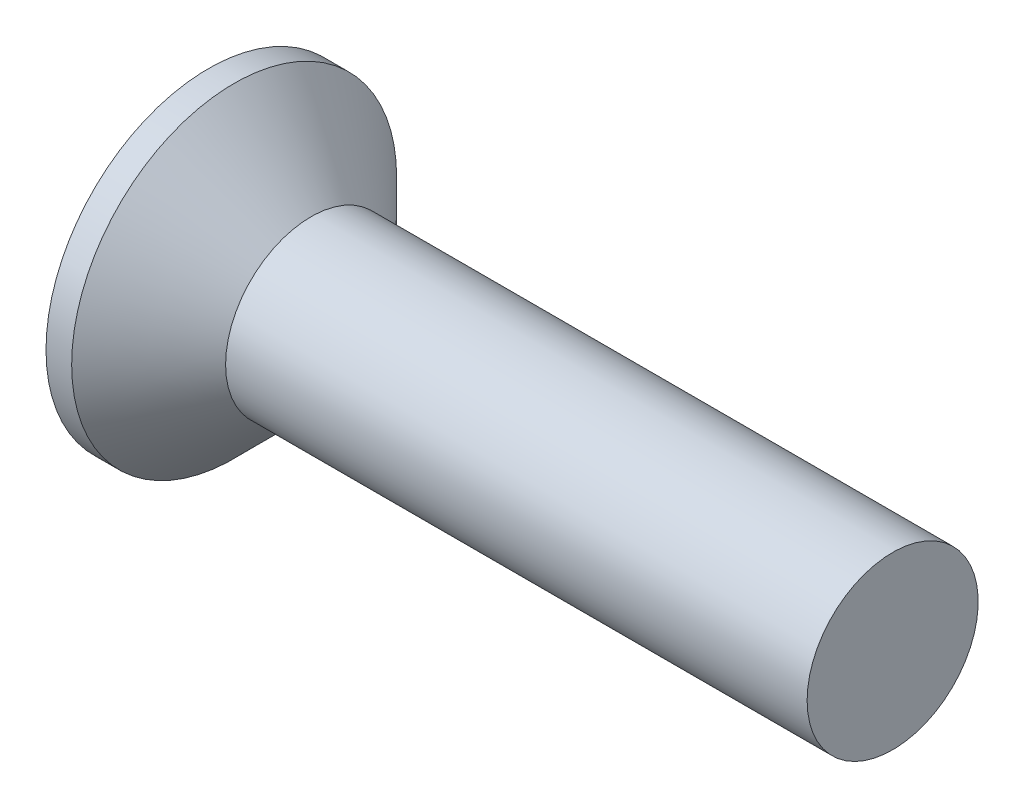
SolidWorks part; units mm, degrees
revolve "Base-Revolve" add sketch "BodySke" angle 360 about L5
sketch "BodySke" plane through (0, 0, 0) normal (0, 0, 1) x (1, 0, 0)
  line L0 (0, 0) -> (0, 1.9)
  line L1 (0, 1.9) -> (0.3, 1.9)
  line L2 (1.2, 1) -> (8, 1)
  line L3 (8, 1) -> (8, 0)
  line L4 (8, 0) -> (0, 0)
  line L5 (-6.35, 0) -> (82.55, 0) construction
  line L6 (1.2, -1) -> (8, -1) construction
  line L7 (0.3, -1.9) -> (1.2, -1) construction
  line L8 (0.3, 1.9) -> (1.2, 1)
  line L9 (0, -1.9) -> (0.3, -1.9) construction
  line L10 (1.6, 2.5875) -> (1.6, -6.9375) construction
  line L11 (5, 6.35) -> (5, -3.175) construction
  dimension "Diameter" = 2
  dimension "Length" = 8
  dimension "Head_ht" = 1.2
  dimension "Head_dia" = 3.8
  dimension "Head_ang" = 90
  dimension "D6" = 0.3
  dimension "Advance" = 0.4
cosmetic thread "ThreadCosmetic" [suppressed] parameters "Thread_length"=6.4, "Thread_minor"=1.548
extrude "Slot" [suppressed] cut sketch "Sketch2" against normal blind 0.6
sketch "Sketch2" plane through (0, 0, 0) normal (-1, 0, 0) x (0, 0, 1)
  line L0 (-1.9, -0.35) -> (1.9, -0.35)
  line L1 (-1.9, -0.35) -> (-1.9, 0.35)
  line L2 (1.9, 0.35) -> (-1.9, 0.35)
  line L3 (1.9, 0.35) -> (1.9, -0.35)
  dimension "Slot_width" = 0.7
  dimension "D1" = 0.35
  dimension "D2" = 3.8
  dimension "D3" = 1.9
ref_plane "Plane1" through (0, 0, 0) normal (0, 0, 1) x (1, 0, 0)
ref_plane "Plane2" through (0, 0, 0) normal (0, 1, 0) x (1, 0, 0)
ref_plane "Plane3" through (0, 0, 0) normal (1, 0, 0) x (0, 0, -1)
sketch "Sketch3" plane through (0, 0, 0) normal (-1, 0, 0) x (0, 0, 1)
  line L0 (-0.265, 1.07) -> (0.265, 1.07)
  line L1 (0.265, 1.07) -> (0.265, -1.07)
  line L2 (0.265, -1.07) -> (-0.265, -1.07)
  line L3 (-0.265, -1.07) -> (-0.265, 1.07)
  dimension "Cross_dia" = 2.14
  dimension "Cross_width" = 0.53
  dimension "D1" = 1.07
  dimension "D2" = 0.265
ref_plane "Plane4" through (1.54, 0, 0) normal (-1, 0, 0) x (0, 0, 1)
sketch "Sketch4" plane through (1.54, 0, 0) normal (-1, 0, 0) x (0, 0, 1)
  line L0 (-0.1325, 0.1325) -> (0.1325, 0.1325)
  line L3 (0.1325, 0.1325) -> (0.1325, -0.1325)
  line L4 (0.1325, -0.1325) -> (-0.1325, -0.1325)
  line L5 (-0.1325, -0.1325) -> (-0.1325, 0.1325)
  dimension "D2" = 0.265
  dimension "D1" = 0.265
  dimension "D3" = 0.1325
  dimension "D4" = 0.1325
loft "Cross" [suppressed] cut profiles "Sketch3", "Sketch4"
pattern_circular "CirPattern1" [suppressed] count 2 every 90 about axis through (-6.35, 0, 0) along (1, 0, 0)
sketch "ThdSchSke" plane through (0, 0, 0) normal (0, 0, 1) x (1, 0, 0)
  line L0 (5, -0.774) -> (4.8418, -1)
  line L1 (5, -0.774) -> (5.1582, -1)
  line L2 (5.1582, -1) -> (5.1582, -1.25)
  line L3 (-3.175, 0) -> (5.1513, 0) construction
  line L5 (5.1582, -1.25) -> (4.8418, -1.25)
  line L6 (4.8418, -1.25) -> (4.8418, -1)
  line L7 (0, 1.9) -> (0, -1.9) construction
  dimension "Diameter" = 2
  dimension "Thread_minor" = 1.548
  dimension "Start" = 1.6
revolve "ThreadSchematic" [suppressed] cut sketch "ThdSchSke" angle 360 about L3
pattern_linear "ThdSchPat" [suppressed]
equation "\"D1@Sketch3\" = \"Cross_dia@Sketch3\" / 2"
equation "\"D2@Sketch3\" = \"Cross_width@Sketch3\" / 2"
equation "\"D1@Sketch4\" = \"Cross_width@Sketch3\" *.5"
equation "\"D2@Sketch4\" = \"D1@Sketch4\""
equation "\"D4@Sketch4\" = \"D2@Sketch4\" / 2"
equation "\"D3@Sketch4\" = \"D1@Sketch4\" / 2"
equation "\"D1@Sketch2\" = \"Slot_width@Sketch2\" / 2"
equation "\"D2@Sketch2\" = \"Head_dia@BodySke\""
equation "\"D3@Sketch2\" = \"D2@Sketch2\" / 2"
equation "\"Thread_length@ThreadCosmetic\" = ((sgn( (\"Length@BodySke\" - \"Advance@BodySke\" - \"Head_ht@BodySke\" ) - \"Thread_nom@BodySke\" )-1)*( (\"Length@BodySke\" - \"Advance@BodySke\" - \"Head_ht@BodySke\" ) - \"Thread_nom@BodySke\" ))/-2+ \"Thread_nom@BodySke\""
equation "\"Thread_minor@ThdSchSke\" = \"Thread_minor@ThreadCosmetic\""
equation "\"Diameter@ThdSchSke\" = \"Diameter@BodySke\""
equation "\"Overcut@ThdSchSke\" = \"Diameter@BodySke\" * 1.25"
equation "\"Start@ThdSchSke\" = 0.000001 + \"Length@BodySke\" - \"Thread_length@ThreadCosmetic\"  '---Countersunk---"
equation "\"Num_threads@ThdSchPat\" = int( \"Thread_length@ThreadCosmetic\" / \"Advance@BodySke\" + 0.999 )  + 1"
equation "\"Advance@ThdSchPat\" = \"Thread_length@ThreadCosmetic\" /  (\"Num_threads@ThdSchPat\" - 1) 'relax it"
